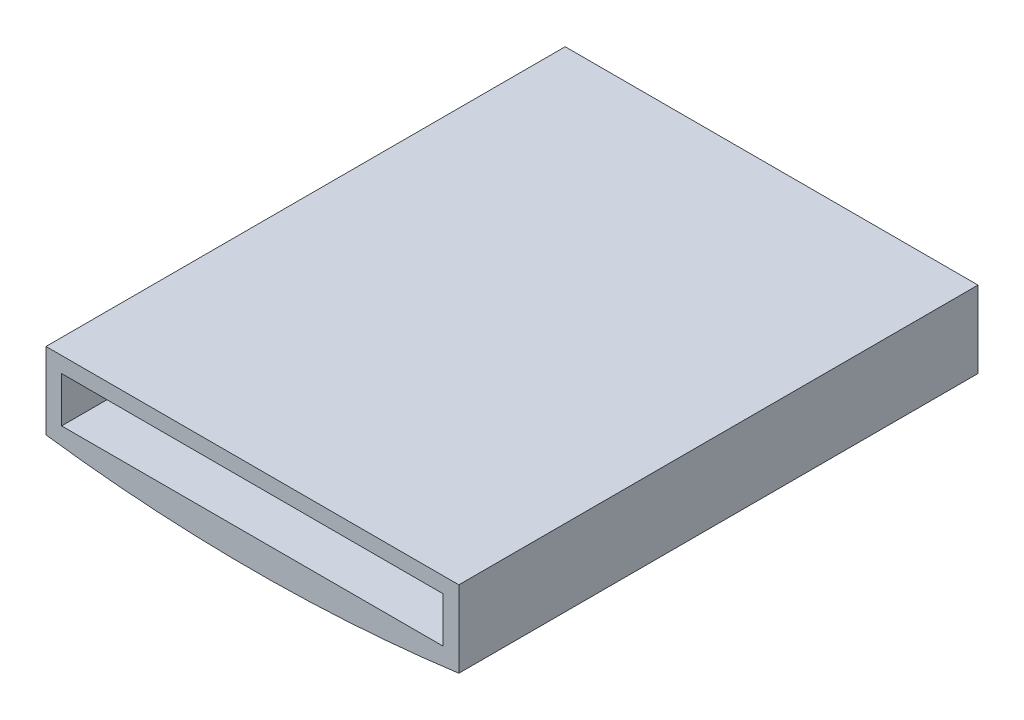
SolidWorks part; units mm, degrees
ref_plane "Front Plane" through (0, 0, 0) normal (0, 0, 1) x (1, 0, 0)
ref_plane "Top Plane" through (0, 0, 0) normal (0, 1, 0) x (1, 0, 0)
ref_plane "Right Plane" through (0, 0, 0) normal (1, 0, 0) x (0, 0, -1)
sketch "Sketch1" plane through (0, 0, 0) normal (0, 0, 1) x (1, 0, 0)
  line L2 (0, 0) -> (0, 49)
  line L3 (0, 49) -> (264, 49)
  line L4 (264, 0) -> (264, 49)
  line L5 (10, 39) -> (254, 39)
  line L6 (10, 39) -> (10, 10)
  line L7 (10, 10) -> (254, 10)
  line L8 (254, 39) -> (254, 10)
  arc A0 (0, 0) -> (264, 0) centre (132, 990.6192) ccw
  point P6 (132, -8.7558)
  dimension "D3" = 29
  dimension "D1" = 264
  dimension "D2" = 49
  dimension "D4" = 10
  dimension "D5" = 244
  dimension "D6" = 10
extrude "Boss-Extrude1" add sketch "Sketch1" along normal mid plane 332
sketch "Sketch3" plane through (0, 0, 0) normal (0, 0, 1) x (1, 0, 0)
  line L0 (0, 49) -> (0, 0) construction
  line L1 (0, 10) -> (264, 10)
  line L2 (0, 10) -> (0, -20.5561)
  line L3 (0, -20.5561) -> (264, -20.5561)
  line L4 (264, 10) -> (264, -20.5561)
extrude "Cut-Extrude2" cut sketch "Sketch3" against normal mid plane 302
sketch "Sketch4" plane through (0, 10, 0) normal (0, -1, 0) x (-1, 0, 0)
  line L1 (0, -151) -> (-264, -151)
  line L2 (0, -151) -> (0, 151)
  line L3 (0, 151) -> (-264, 151)
  line L4 (-264, -151) -> (-264, 151)
  point P6 (131996.0265, -500000)
extrude "Boss-Extrude2" add sketch "Sketch4" along normal blind 10
